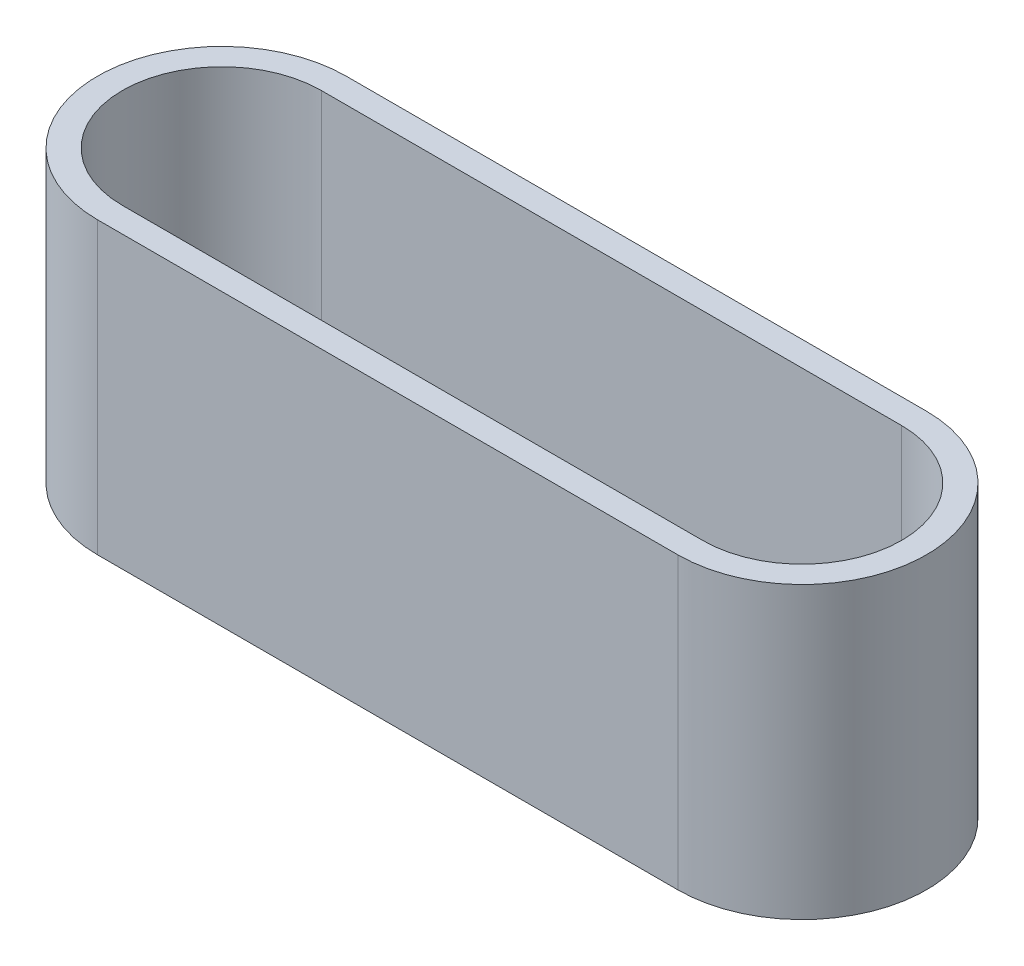
SolidWorks part; units mm, degrees
ref_plane "Front Plane" through (0, 0, 0) normal (0, 0, 1) x (1, 0, 0)
ref_plane "Top Plane" through (0, 0, 0) normal (0, 1, 0) x (1, 0, 0)
ref_plane "Right Plane" through (0, 0, 0) normal (1, 0, 0) x (0, 0, -1)
sketch "Sketch1" plane through (0, 0, 0) normal (0, 1, 0) x (1, 0, 0)
  line L0 (-35, 0) -> (35, 0) construction
  line L1 (-35, 12) -> (35, 12)
  line L2 (-35, -12) -> (35, -12)
  line L3 (-35, 15) -> (35, 15)
  line L4 (-35, -15) -> (35, -15)
  arc A0 (-35, 12) -> (-35, -12) centre (-35, 0) ccw
  arc A1 (35, -12) -> (35, 12) centre (35, 0) ccw
  arc A2 (35, -15) -> (35, 15) centre (35, 0) ccw
  arc A3 (-35, 15) -> (-35, -15) centre (-35, 0) ccw
  point P2 (0, 0)
  dimension "D1" = 70
  dimension "D2" = 24
  dimension "D3" = 3
extrude "Boss-Extrude1" add sketch "Sketch1" along normal blind 35
